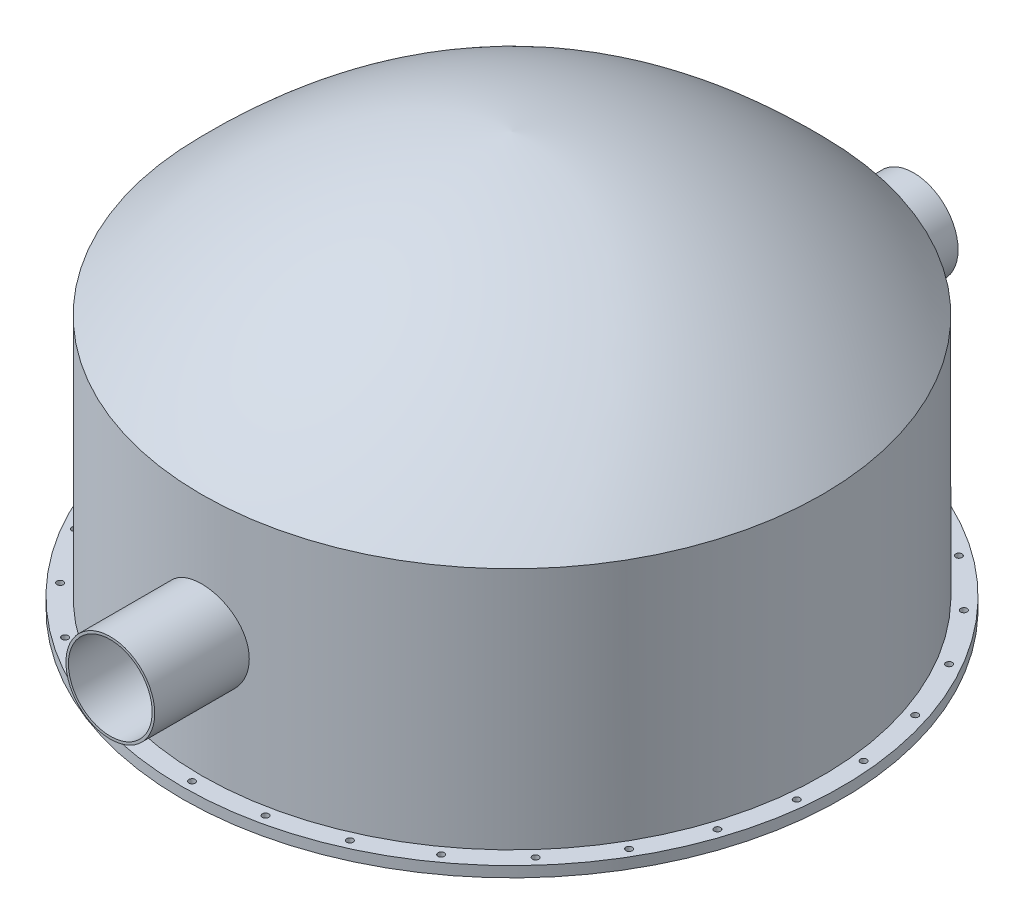
SolidWorks part; units mm, degrees
ref_plane "Front Plane" through (0, 0, 0) normal (0, 0, 1) x (1, 0, 0)
ref_plane "Top Plane" through (0, 0, 0) normal (0, 1, 0) x (1, 0, 0)
ref_plane "Right Plane" through (0, 0, 0) normal (1, 0, 0) x (0, 0, -1)
sketch "Sketch2" plane through (0, 0, 0) normal (1, 0, 0) x (0, 0, -1)
  line L0 (0, 0) -> (2427.7874, 0) construction
  line L1 (0, 0) -> (0, 2804.3081) construction
  line L2 (-2081.1295, -171.115) -> (-2081.1295, 0)
  line L3 (-2130.0195, -171.115) -> (-2130.0195, -1671.115)
  line L4 (-2130.0195, -1671.115) -> (-2262.0195, -1671.115)
  line L5 (-2130.0195, -171.115) -> (-2130.0195, 0)
  line L7 (-2262.0195, -1671.115) -> (-2262.0195, -1744.115)
  line L8 (-2262.0195, -1744.115) -> (-2081.1295, -1744.115)
  line L9 (0, 1093.3) -> (0, 1044.41)
  line L10 (-2081.1295, -1744.115) -> (-2081.1295, -171.115)
  spline S0 degree 2 poles (-2130.0195, 0) (-1162.829, 997.3651) (0, 1093.3) knots 0 0 0 0.824504 0.824504 0.824504
  spline S2 degree 2 poles (-2081.1295, 0) (-1041.8652, 973.9069) (0, 1044.41) knots 0 0 0 1 1 1
  dimension "D1" = 48.89
  dimension "D2" = 1093.3
  dimension "D3" = 1500
  dimension "D4" = 48.89
  dimension "D5" = 132
  dimension "D6" = 73
  dimension "D7" = 2081.1295
revolve "Revolve3" add sketch "Sketch2" angle 360 about L9
ref_plane "Plane1" through (0, 0, -2757) normal (0, 0, 1) x (1, 0, 0)
sketch "Sketch5" plane through (0, 0, -2757) normal (0, 0, 1) x (1, 0, 0)
  circle A0 centre (0, -835.5575) radius 304.8
  dimension "D1" = 609.6
extrude "Boss-Extrude1" add sketch "Sketch5" along normal blind 740
mirror "Mirror1" about plane through (0, 0, 0) normal (0, 0, 1) of "Boss-Extrude1"
sketch "Sketch6" plane through (0, 0, -2757) normal (0, 0, 1) x (1, 0, 0)
  circle A0 centre (0, -835.5575) radius 287.4
  dimension "D1" = 574.8
extrude "Cut-Extrude2" cut sketch "Sketch6" along normal blind 10000
ref_plane "Plane2" through (0, -1744.115, 0) normal (0, -1, 0) x (1, 0, 0)
sketch "Sketch7" plane through (0, -1744.115, 0) normal (0, -1, 0) x (1, 0, 0)
  circle A0 centre (0, 0) radius 2056.6885
extrude "Cut-Extrude3" cut sketch "Sketch7" against normal blind 1400
sketch "Sketch9" plane through (0, -1744.115, 0) normal (0, -1, 0) x (1, 0, 0)
  circle A0 centre (0, 0) radius 2081.1295
extrude "Cut-Extrude4" cut sketch "Sketch9" against normal blind 1300
sketch "Sketch11" plane through (0, -1744.115, 0) normal (0, -1, 0) x (1, 0, 0)
  line L0 (0, 0) -> (0, 2196.0195) construction
  circle A1 centre (0, 2196.0195) radius 22
  circle A2 centre (456.5781, 2148.0312) radius 22
  circle A3 centre (893.2016, 2006.1636) radius 22
  circle A4 centre (1290.7879, 1776.6171) radius 22
  circle A5 centre (1631.9605, 1469.4239) radius 22
  circle A6 centre (1901.8087, 1098.0097) radius 22
  circle A7 centre (2088.5387, 678.6073) radius 22
  circle A8 centre (2183.9895, 229.5465) radius 22
  circle A9 centre (2183.9895, -229.5465) radius 22
  circle A10 centre (2088.5387, -678.6073) radius 22
  circle A11 centre (1901.8087, -1098.0098) radius 22
  circle A12 centre (1631.9605, -1469.4239) radius 22
  circle A13 centre (1290.7879, -1776.6171) radius 22
  circle A14 centre (893.2016, -2006.1636) radius 22
  circle A15 centre (456.5781, -2148.0312) radius 22
  circle A16 centre (0, -2196.0195) radius 22
  circle A17 centre (-456.5781, -2148.0312) radius 22
  circle A18 centre (-893.2016, -2006.1636) radius 22
  circle A19 centre (-1290.7879, -1776.6171) radius 22
  circle A20 centre (-1631.9605, -1469.4239) radius 22
  circle A21 centre (-1901.8087, -1098.0097) radius 22
  circle A22 centre (-2088.5387, -678.6073) radius 22
  circle A23 centre (-2183.9895, -229.5465) radius 22
  circle A24 centre (-2183.9895, 229.5465) radius 22
  circle A25 centre (-2088.5387, 678.6073) radius 22
  circle A26 centre (-1901.8087, 1098.0098) radius 22
  circle A27 centre (-1631.9605, 1469.4239) radius 22
  circle A28 centre (-1290.7879, 1776.6171) radius 22
  circle A29 centre (-893.2016, 2006.1636) radius 22
  circle A30 centre (-456.5781, 2148.0312) radius 22
  dimension "D2" = 44
  dimension "D1" = 30
  dimension "D3" = 2196.0195
extrude "Cut-Extrude5" cut sketch "Sketch11" against normal blind 500
